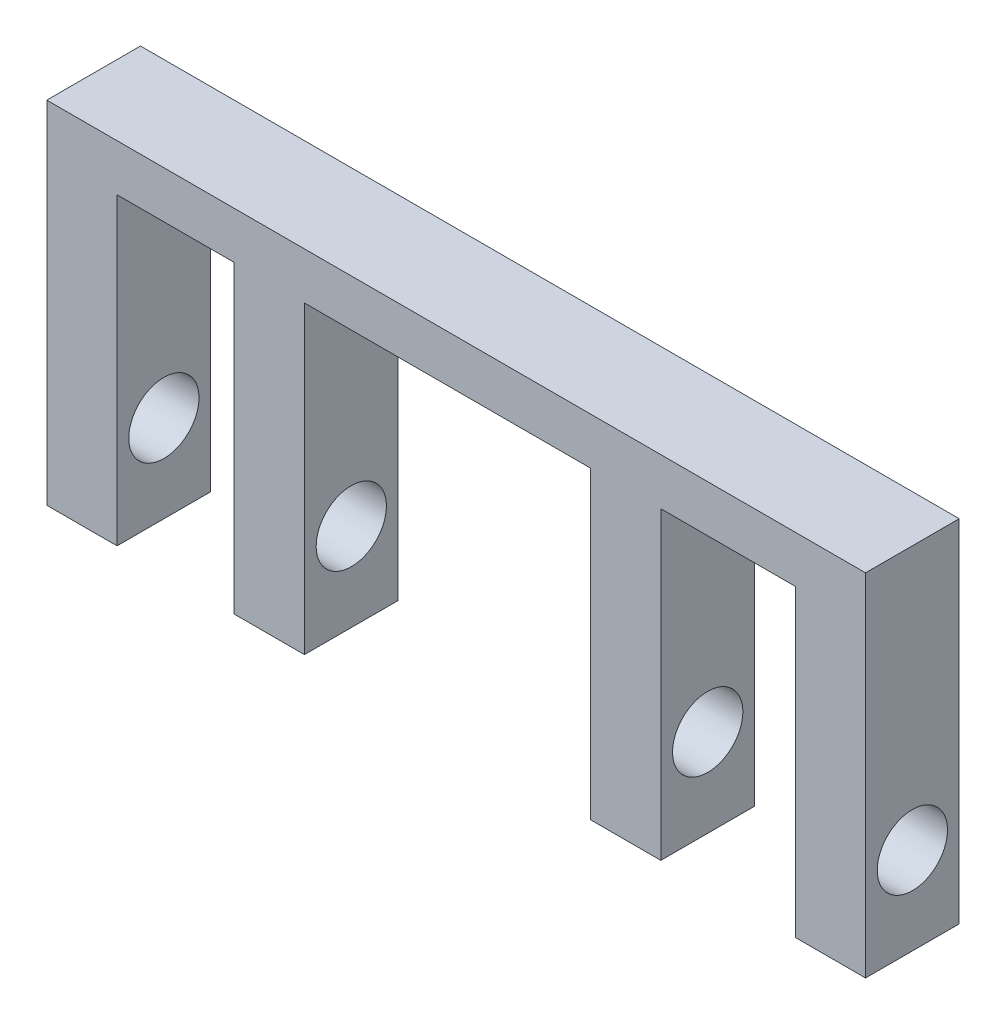
SolidWorks part; units mm, degrees
ref_plane "Front Plane" through (0, 0, 0) normal (0, 0, 1) x (1, 0, 0)
ref_plane "Top Plane" through (0, 0, 0) normal (0, 1, 0) x (1, 0, 0)
ref_plane "Right Plane" through (0, 0, 0) normal (1, 0, 0) x (0, 0, -1)
sketch "Sketch1" plane through (0, 0, 0) normal (0, 0, 1) x (1, 0, 0)
  line L1 (0, 0) -> (349.51, 0)
  line L2 (0, 0) -> (0, 149.79)
  line L3 (0, 149.79) -> (349.51, 149.79)
  line L4 (349.51, 0) -> (349.51, 149.79)
  line L9 (30, 0) -> (319.51, 0)
  line L10 (30, 0) -> (30, 129.79)
  line L11 (30, 129.79) -> (319.51, 129.79)
  line L12 (319.51, 0) -> (319.51, 129.79)
  dimension "D1" = 149.79
  dimension "D2" = 349.51
  dimension "D3" = 30
  dimension "D4" = 30
  dimension "D5" = 20
extrude "Boss-Extrude1" add sketch "Sketch1" along normal blind 40 contours L12 L1 L4 L3 L2 L10 L11
sketch "Sketch2" plane through (0, 129.79, 0) normal (0, -1, 0) x (1, 0, 0)
  line L0 (30, 40) -> (80, 40)
  line L1 (30, 40) -> (319.51, 40) construction
  line L2 (30, 0) -> (319.51, 0) construction
  line L3 (80, 40) -> (110, 40)
  line L4 (80, 40) -> (80, 0)
  line L5 (80, 0) -> (110, 0)
  line L6 (110, 40) -> (110, 0)
  line L7 (319.51, 40) -> (262.1283, 40)
  line L9 (0, 40) -> (30, 40)
  line L10 (0, 40) -> (0, 0)
  line L11 (0, 0) -> (30, 0)
  line L12 (30, 40) -> (30, 0)
  line L13 (262.1283, 40) -> (232.1283, 40)
  line L14 (262.1283, 40) -> (262.1283, 0)
  line L15 (262.1283, 0) -> (232.1283, 0)
  line L16 (232.1283, 40) -> (232.1283, 0)
  line M7 (30, 0) -> (319.51, 0)
  line M9 (319.51, 40) -> (30, 40)
  dimension "D1" = 30
  dimension "D2" = 30
extrude "Boss-Extrude2" add sketch "Sketch2" along normal blind 130 contours L6 L4 M9 M7 | L16 L14 M9 M7
sketch "Sketch4" plane through (0, 0, 0) normal (-1, 0, 0) x (0, 0, 1)
  line L0 (20, -0.21) -> (20, 149.79)
  line L1 (40, -0.21) -> (0, -0.21) construction
  line L2 (40, 149.79) -> (0, 149.79) construction
  line L3 (40, 74.895) -> (0, 74.895)
  line L4 (40, 0) -> (40, 149.79) construction
  line L5 (0, 0) -> (0, 149.79) construction
  line L6 (20, 74.79) -> (20, -0.21)
  circle A0 centre (20, 37.29) radius 15
  dimension "D1" = 30
extrude "Cut-Extrude1" cut sketch "Sketch4" against normal blind 410 contours L6 A0 | L6 A0
